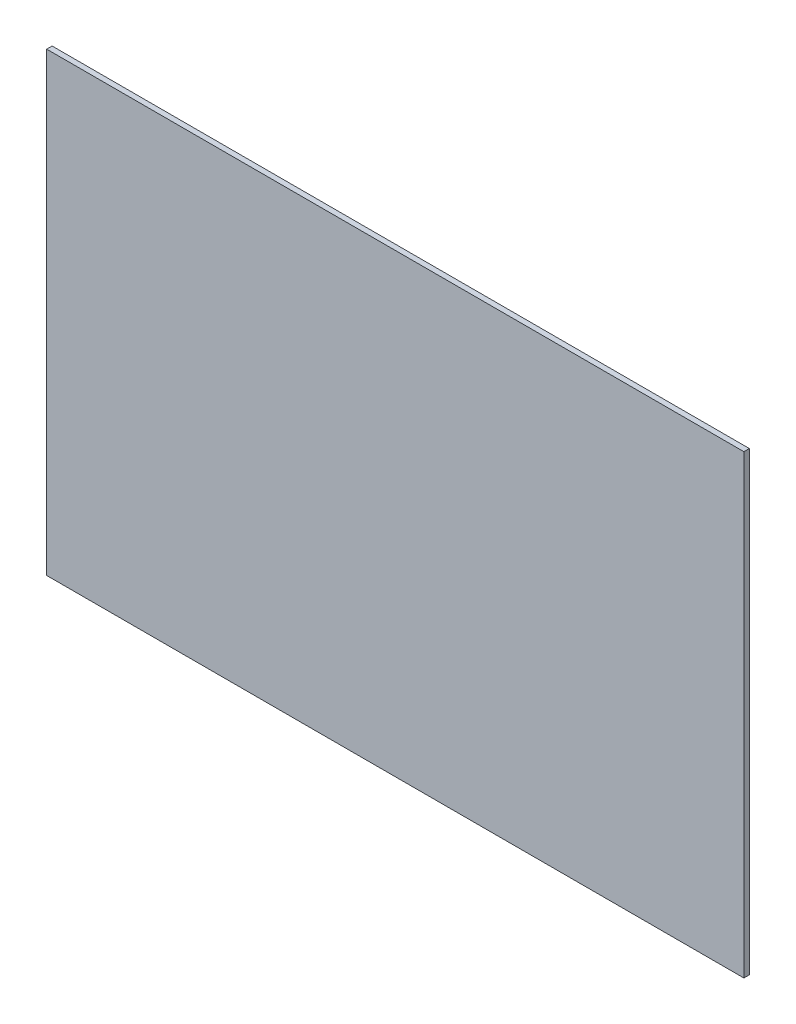
SolidWorks part; units mm, degrees
ref_plane "Plan de face" through (0, 0, 0) normal (0, 0, 1) x (1, 0, 0)
ref_plane "Plan de dessus" through (0, 0, 0) normal (0, 1, 0) x (1, 0, 0)
ref_plane "Plan de droite" through (0, 0, 0) normal (1, 0, 0) x (0, 0, -1)
sketch "Esquisse1" plane through (0, 0, 0) normal (0, 0, 1) x (1, 0, 0)
  line L1 (-416, -272) -> (416, -272)
  line L2 (-416, -272) -> (-416, 272)
  line L3 (-416, 272) -> (416, 272)
  line L4 (416, -272) -> (416, 272)
  line L5 (-416, -272) -> (416, 272) construction
  line L6 (-416, 272) -> (416, -272) construction
  point P0 (0, 0)
  dimension "D1" = 544
  dimension "D2" = 832
extrude "Boss.-Extru.1" add sketch "Esquisse1" along normal blind 6.5
